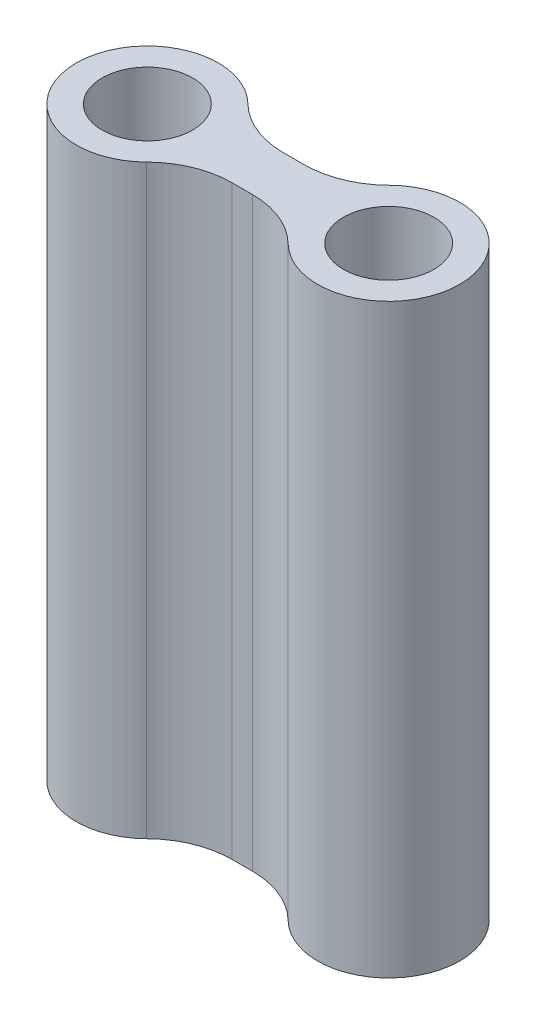
SolidWorks part; units mm, degrees
ref_plane "Front Plane" through (0, 0, 0) normal (0, 0, 1) x (1, 0, 0)
ref_plane "Top Plane" through (0, 0, 0) normal (0, 1, 0) x (1, 0, 0)
ref_plane "Right Plane" through (0, 0, 0) normal (1, 0, 0) x (0, 0, -1)
sketch "Sketch1" plane through (0, 0, 0) normal (0, 1, 0) x (1, 0, 0)
  line L0 (-7.5957, 1.5) -> (-6.4043, 1.5)
  line L1 (-7.5957, -1.5) -> (-6.4043, -1.5)
  circle A0 centre (0, 0) radius 2.625
  arc A2 (-2.8951, -2.9384) -> (-2.8951, 2.9384) centre (0, 0) ccw
  circle A3 centre (-14, 0) radius 2.625
  arc A4 (-11.1049, 2.9384) -> (-11.1049, -2.9384) centre (-14, 0) ccw
  arc A5 (-6.4043, -1.5) -> (-2.8951, -2.9384) centre (-6.4043, -6.5) cw
  arc A6 (-7.5957, -1.5) -> (-11.1049, -2.9384) centre (-7.5957, -6.5) ccw
  arc A7 (-6.4043, 1.5) -> (-2.8951, 2.9384) centre (-6.4043, 6.5) ccw
  arc A8 (-7.5957, 1.5) -> (-11.1049, 2.9384) centre (-7.5957, 6.5) cw
  point P13 (0, 0)
  dimension "D1" = 5.25
  dimension "D2" = 1.5
  dimension "D3" = 5.25
  dimension "D4" = 1.5
  dimension "D8" = 5
  dimension "D5" = 14
  dimension "D6" = 1.5
  dimension "D7" = 1.5
extrude "Boss-Extrude1" add sketch "Sketch1" along normal blind 34
